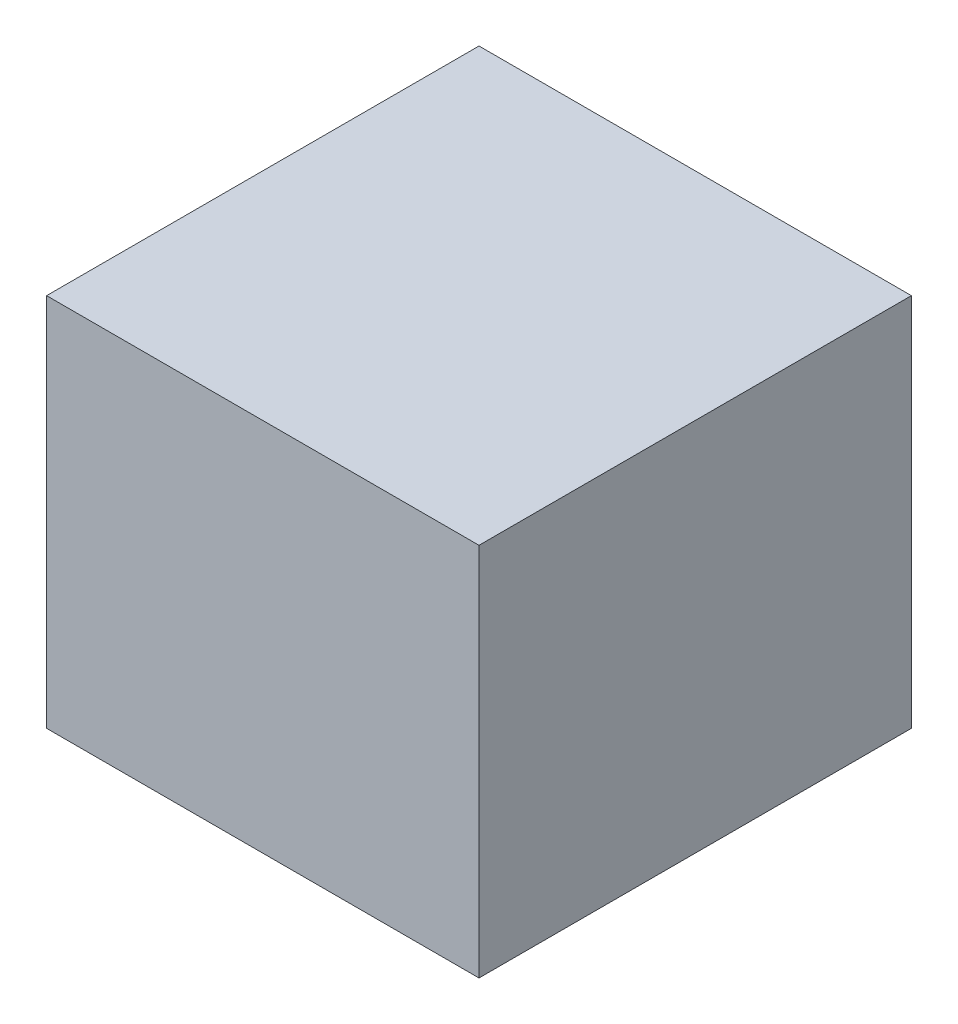
SolidWorks part; units mm, degrees
ref_plane "前视基准面" through (0, 0, 0) normal (0, 0, 1) x (1, 0, 0)
ref_plane "上视基准面" through (0, 0, 0) normal (0, 1, 0) x (1, 0, 0)
ref_plane "右视基准面" through (0, 0, 0) normal (1, 0, 0) x (0, 0, -1)
sketch "草图1" plane through (0, 0, 0) normal (0, 1, 0) x (1, 0, 0)
  line L1 (-37.5, 37.5) -> (37.5, 37.5)
  line L2 (-37.5, 37.5) -> (-37.5, -37.5)
  line L3 (-37.5, -37.5) -> (37.5, -37.5)
  line L4 (37.5, 37.5) -> (37.5, -37.5)
  line L5 (-37.5, 37.5) -> (37.5, -37.5) construction
  line L6 (-37.5, -37.5) -> (37.5, 37.5) construction
  point P0 (0, 0)
  dimension "D1" = 75
  dimension "D2" = 75
extrude "凸台-拉伸1" add sketch "草图1" along normal blind 65
